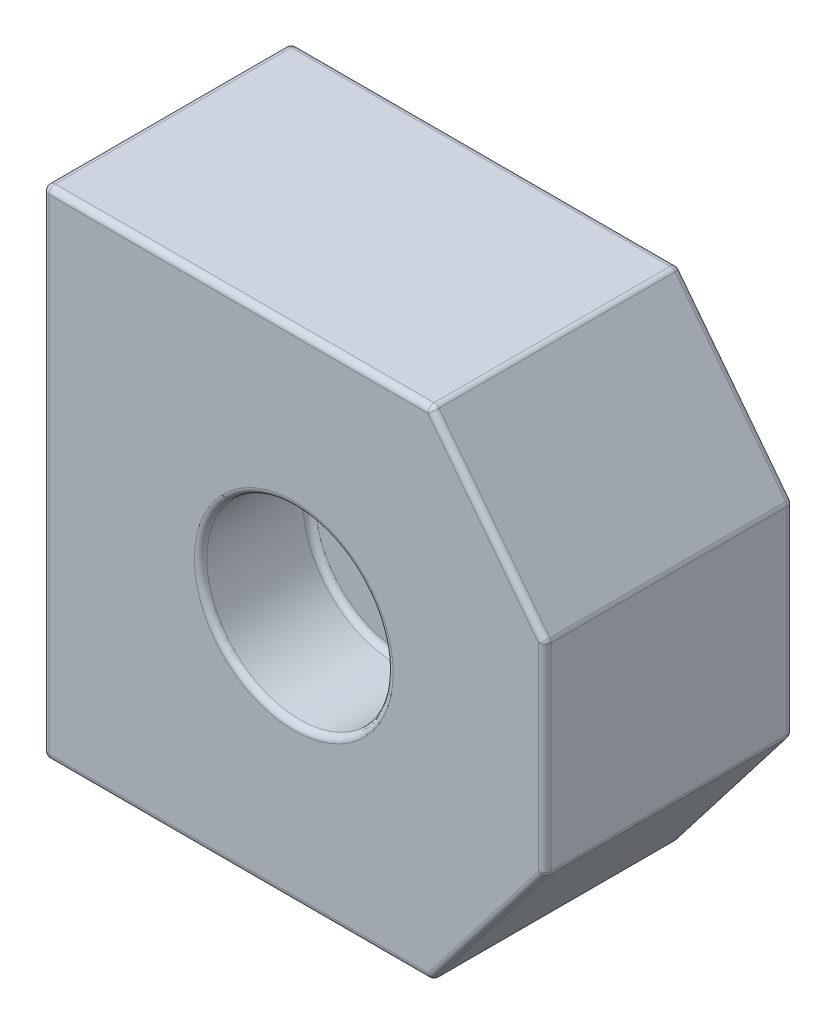
SolidWorks part; units mm, degrees
ref_plane "Front Plane" through (0, 0, 0) normal (0, 0, 1) x (1, 0, 0)
ref_plane "Top Plane" through (0, 0, 0) normal (0, 1, 0) x (1, 0, 0)
ref_plane "Right Plane" through (0, 0, 0) normal (1, 0, 0) x (0, 0, -1)
sketch "Sketch3" plane through (0, 0, 0) normal (0, 0, 1) x (1, 0, 0)
  line L0 (0, 0) -> (0, -32)
  line L1 (0, -32) -> (25, -32)
  line L2 (25, -32) -> (32.3314, -22.5)
  line L3 (32.3314, -22.5) -> (32.3314, -9.5)
  line L4 (32.3314, -9.5) -> (25, 0)
  line L5 (25, 0) -> (0, 0)
  point P7 (32.3314, -16)
  point P8 (0, -16)
  dimension "D1" = 12
  dimension "D2" = 12
  dimension "D3" = 32
  dimension "D4" = 13
  dimension "D5" = 25
extrude "Boss-Extrude1" add sketch "Sketch3" along normal blind 16
sketch "Sketch4" plane through (0, 0, 16) normal (0, 0, 1) x (1, 0, 0)
  line L0 (0, 0) -> (0, -32) construction
  line L1 (0, -16) -> (32.3314, -16) construction
  line L2 (32.3314, -22.5) -> (32.3314, -9.5) construction
  circle A0 centre (16.1657, -16) radius 6
  point P6 (0, -16)
  point P11 (16.1657, -16)
  dimension "D1" = 12
extrude "Cut-Extrude1" cut sketch "Sketch4" against normal blind 7
sketch "Sketch5" plane through (0, 0, 9) normal (0, 0, 1) x (1, 0, 0)
  circle A0 centre (16.1657, -16) radius 3.2
  circle A1 centre (16.1657, -16) radius 6
  circle A2 centre (16.1657, -16) radius 6
  dimension "D2" = 6.4
  dimension "D1" = 0
extrude "Cut-Extrude2" cut sketch "Sketch5" against normal blind 11 contours A0
fillet "Fillet1" radius 0.4 22 edges at (22.1657, -16, 9) (19.3657, -16, 9) (28.6657, -4.75, 0) (32.3314, -9.5, 8) (32.3314, -16, 0) (12.5, -32, 0) (25, -32, 8) (32.3314, -22.5, 8) (28.6657, -27.25, 0) (0, -32, 8) (0, -16, 0) (28.6657, -4.75, 16) (32.3314, -16, 16) (28.6657, -27.25, 16) (12.5, -32, 16) (0, -16, 16) (22.1657, -16, 16) (25, 0, 8) (12.5, 0, 16) (0, 0, 8) (12.5, 0, 0) (19.3657, -16, 0)
